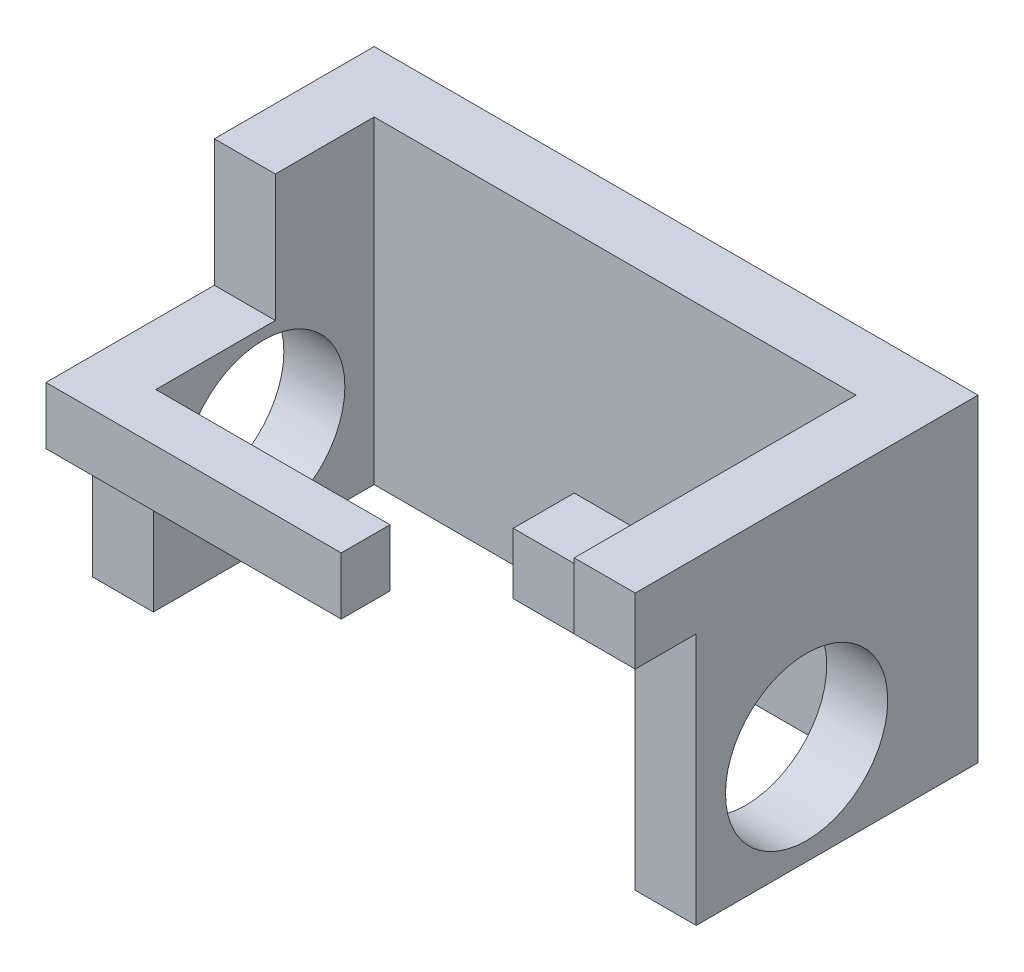
SolidWorks part; units mm, degrees
ref_plane "Alzado" through (0, 0, 0) normal (0, 0, 1) x (1, 0, 0)
ref_plane "Planta" through (0, 0, 0) normal (0, 1, 0) x (1, 0, 0)
ref_plane "Vista lateral" through (0, 0, 0) normal (1, 0, 0) x (0, 0, -1)
sketch "Croquis2" plane through (0, 0, 0) normal (0, 1, 0) x (1, 0, 0)
  line L1 (0, 0) -> (-49.5, 0)
  line L2 (0, 0) -> (0, -26.9)
  line L3 (0, -26.9) -> (-49.5, -26.9)
  line L4 (-49.5, 0) -> (-49.5, -26.9)
  dimension "D1" = 49.5
  dimension "D2" = 26.9
extrude "Saliente-Extruir1" add sketch "Croquis2" along normal blind 26.1
sketch "Croquis6" plane through (0, 26.1, 0) normal (0, 1, 0) x (1, 0, 0)
  line L4 (-44.5, -21.9) -> (-44.5, -22.9)
  line L5 (-44.5, -22.9) -> (-25.3, -22.9)
  line L6 (-25.3, -22.9) -> (-25.3, -26.9)
  line L7 (-49.5, -26.9) -> (0, -26.9) construction
  line L8 (-5, -21.9) -> (-5, -5)
  line L9 (-5, -5) -> (-44.5, -5)
  line L10 (-44.5, -5) -> (-44.5, -21.9)
  line L11 (-44.5, -21.9) -> (-5, -21.9)
  line L12 (-5, -21.9) -> (-5, -5)
  line L13 (-5, -5) -> (-44.5, -5)
  line L14 (-44.5, -5) -> (-44.5, -21.9)
  line L16 (-25.3, -26.9) -> (-5, -26.9)
  line L17 (-5, -26.9) -> (-5, -21.9)
  dimension "D2" = 1
  dimension "D3" = 19.2
  dimension "D1" = 5
extrude "Cortar-Extruir2" cut sketch "Croquis6" against normal up to surface (26.1 mm away) up to face at (-24.75, 0, 13.45)
sketch "Croquis8" plane through (0, 0, 0) normal (1, 0, 0) x (0, 0, -1)
  line L0 (-26.9, 8.15) -> (-14.05, 8.15) construction
  line L1 (-26.9, 26.1) -> (-26.9, 0) construction
  line L2 (-14.05, 8.15) -> (-14.05, 0) construction
  line L3 (-26.9, 0) -> (0, 0) construction
  circle A0 centre (-14.05, 8.15) radius 6.65
  dimension "D1" = 12.85
  dimension "D2" = 8.15
sketch "Croquis9" plane through (-44.5, 0, 0) normal (1, 0, 0) x (0, 0, -1)
  circle A0 centre (-14.05, 8.15) radius 6.65 construction
  circle A1 centre (-14.05, 8.15) radius 6.65
extrude "Cortar-Extruir4" cut sketch "Croquis9" against normal up to next
extrude "Cortar-Extruir5" cut sketch "Croquis8" against normal up to next
sketch "Croquis10" plane through (0, 0, 26.9) normal (0, 0, 1) x (1, 0, 0)
  line L0 (-25.3, 0) -> (-25.3, 26.1) construction
  line L1 (-49.5, 0) -> (-25.3, 0)
  line L2 (-49.5, 0) -> (-49.5, 11)
  line L3 (-49.5, 11) -> (-25.3, 11)
  line L4 (-25.3, 0) -> (-25.3, 11)
  dimension "D1" = 11
sketch "Croquis11" plane through (0, 26.1, 0) normal (0, 1, 0) x (1, 0, 0)
  line L0 (-47.0606, 0) -> (-47.0606, -13.1) construction
  line L1 (0, 0) -> (-49.5, 0) construction
  line L2 (-44.5, -13.1) -> (-49.5, -13.1)
  line L3 (-44.5, -5) -> (-44.5, -22.9) construction
  line L4 (-49.5, 0) -> (-49.5, -26.9) construction
  line L5 (-49.5, -13.1) -> (-49.5, -26.9)
  line L6 (-49.5, -26.9) -> (-25.3, -26.9)
  line L7 (-25.3, -26.9) -> (-25.3, -22.9)
  line L8 (-44.5, -22.9) -> (-25.3, -22.9) construction
  line L9 (-25.3, -22.9) -> (-25.3, -26.9) construction
  line L10 (-25.3, -22.9) -> (-44.5, -22.9)
  line L11 (-44.5, -22.9) -> (-44.5, -13.1)
  dimension "D1" = 13.1
extrude "Cortar-Extruir6" cut sketch "Croquis11" against normal blind 10.4
extrude "Cortar-Extruir7" cut sketch "Croquis10" against normal blind 3.8
sketch "Croquis13" plane through (0, 0, 22.9) normal (0, 0, -1) x (-1, 0, 0)
  line L0 (25.3, 11) -> (49.5, 11) construction
  line L1 (25.3, 11) -> (44.5, 11)
  line L3 (44.5, 0) -> (44.5, 15.7) construction
  line L4 (25.3, 0) -> (44.5, 0)
  line L5 (25.3, 0) -> (25.3, 11)
  line L6 (25.3, 11) -> (44.5, 11)
  line L7 (44.5, 0) -> (44.5, 11)
  line M2 (25.3, 15.7) -> (25.3, 0)
  line M3 (25.3, 0) -> (44.5, 0)
  line M4 (44.5, 0) -> (44.5, 15.7)
extrude "Cortar-Extruir8" cut sketch "Croquis13" against normal up to surface (0.2 mm away) contours L1 M2 M3 M4 up to face at (-37.4, 5.5, 23.1)
sketch "Croquis14" plane through (0, 0, 0) normal (1, 0, 0) x (0, 0, -1)
  line L0 (-26.9, 0) -> (-26.9, 20.7)
  line L1 (-26.9, 0) -> (0, 0) construction
  line L4 (-26.9, 0) -> (-23.1, 0)
  line L7 (-26.9, 26.1) -> (-26.9, 0) construction
  line L9 (-23.1, 20.7) -> (-23.1, 0)
  line L14 (-26.9, 20.7) -> (-23.1, 20.7)
  dimension "D1" = 20.7
  dimension "D2" = 3.8
extrude "Cortar-Extruir9" cut sketch "Croquis14" against normal up to next
sketch "Croquis15" plane through (0, 0, 23.1) normal (0, 0, 1) x (1, 0, 0)
  line L1 (-15, 20.7) -> (-15, 15.7)
  line L2 (-15, 15.7) -> (-5, 15.7)
  line L3 (-5, 20.7) -> (-5, 0) construction
  line L7 (-15, 20.7) -> (-5, 20.7)
  line L8 (-5, 20.7) -> (-5, 26.1) construction
  line L9 (-5, 20.7) -> (-5, 15.7)
  dimension "D2" = 5
extrude "Saliente-Extruir2" add sketch "Croquis15" against normal blind 5
sketch "Croquis16" plane through (0, 0, 26.9) normal (0, 0, 1) x (1, 0, 0)
  line L4 (-5, 26.1) -> (-5, 20.7)
  line L5 (-5, 20.7) -> (0, 20.7)
  line L6 (0, 20.7) -> (0, 26.1)
  line L7 (0, 26.1) -> (-5, 26.1)
  line L8 (-5, 26.1) -> (-5, 20.7)
  line L9 (-5, 20.7) -> (0, 20.7)
  line L10 (0, 20.7) -> (0, 26.1)
  line L11 (0, 26.1) -> (-5, 26.1)
  dimension "D1" = 0
extrude "Saliente-Extruir3" add sketch "Croquis16" along normal blind 1.2
